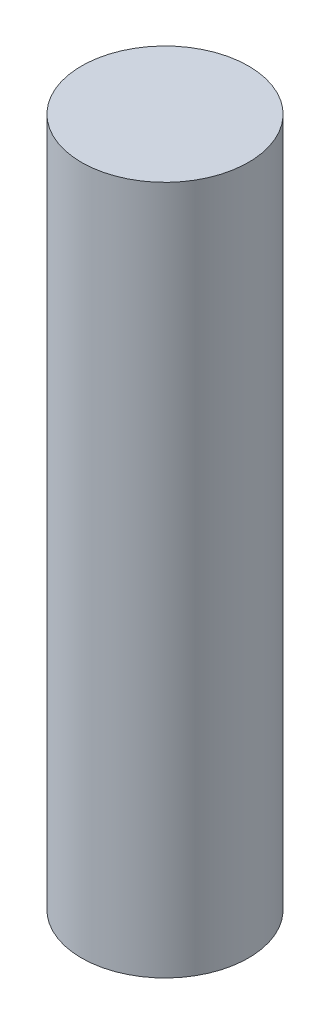
SolidWorks part; units mm, degrees
material "PE High Density"
ref_plane "Front Plane" through (0, 0, 0) normal (0, 0, 1) x (1, 0, 0)
ref_plane "Top Plane" through (0, 0, 0) normal (0, 1, 0) x (1, 0, 0)
ref_plane "Right Plane" through (0, 0, 0) normal (1, 0, 0) x (0, 0, -1)
sketch "Sketch1" plane through (0, 0, 0) normal (0, 1, 0) x (1, 0, 0)
  circle A0 centre (0, 0) radius 20
  dimension "D1" = 40
extrude "Boss-Extrude1" add sketch "Sketch1" along normal blind 165
scale "Scale1" scale about centroid uniform scaling yes scale factor 0.75
